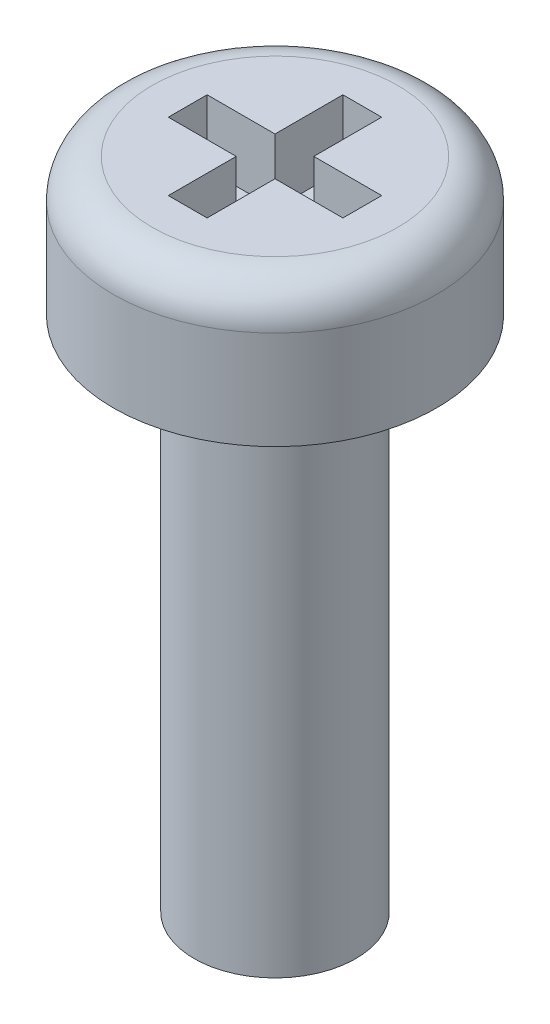
SolidWorks part; units mm, degrees
material "1023 Carbon Steel Sheet (SS)"
ref_plane "Front Plane" through (0, 0, 0) normal (0, 0, 1) x (1, 0, 0)
ref_plane "Top Plane" through (0, 0, 0) normal (0, 1, 0) x (1, 0, 0)
ref_plane "Right Plane" through (0, 0, 0) normal (1, 0, 0) x (0, 0, -1)
sketch "Sketch1" plane through (0, 0, 0) normal (0, 0, 1) x (1, 0, 0)
  line L0 (0, 0) -> (0, 10.12)
  line L1 (0, 10.12) -> (2.5, 10.12)
  line L2 (2.5, 10.12) -> (2.5, 8)
  line L3 (2.5, 8) -> (1.25, 8)
  line L4 (1.25, 8) -> (1.25, 0)
  line L5 (1.25, 0) -> (0, 0)
  dimension "D1" = 2.5
  dimension "D2" = 8
  dimension "D3" = 1.25
  dimension "D4" = 2.12
revolve "Revolve1" add sketch "Sketch1" angle 360 about L0
sketch "Sketch2" plane through (0, 10.12, 0) normal (0, 1, 0) x (1, 0, 0)
  line L0 (-0.3, 0.3) -> (-1.35, 0.3)
  line L1 (1.35, -0.3) -> (0.3, -0.3)
  line L2 (1.35, -0.3) -> (1.35, 0.3)
  line L3 (1.35, 0.3) -> (0.3, 0.3)
  line L4 (-1.35, -0.3) -> (-1.35, 0.3)
  line L5 (1.35, -0.3) -> (-1.35, 0.3) construction
  line L6 (1.35, 0.3) -> (-1.35, -0.3) construction
  line L7 (0.3, -1.35) -> (-0.3, -1.35)
  line L8 (0.3, -1.35) -> (0.3, -0.3)
  line L9 (0.3, 1.35) -> (-0.3, 1.35)
  line L10 (-0.3, -1.35) -> (-0.3, -0.3)
  line L11 (0.3, -1.35) -> (-0.3, 1.35) construction
  line L12 (0.3, 1.35) -> (-0.3, -1.35) construction
  line L13 (-0.3, 0.3) -> (-0.3, 1.35)
  line L15 (0.3, 0.3) -> (0.3, 1.35)
  line L16 (-0.3, -0.3) -> (-1.35, -0.3)
  point P0 (0, 0)
  point P6 (0, 0)
  dimension "D1" = 2.7
  dimension "D2" = 2.7
  dimension "D3" = 0.6
  dimension "D4" = 0.6
extrude "Cut-Extrude1" cut sketch "Sketch2" against normal blind 1
fillet "Fillet1" radius 0.6 1 edges at (0, 10.12, -2.5)
